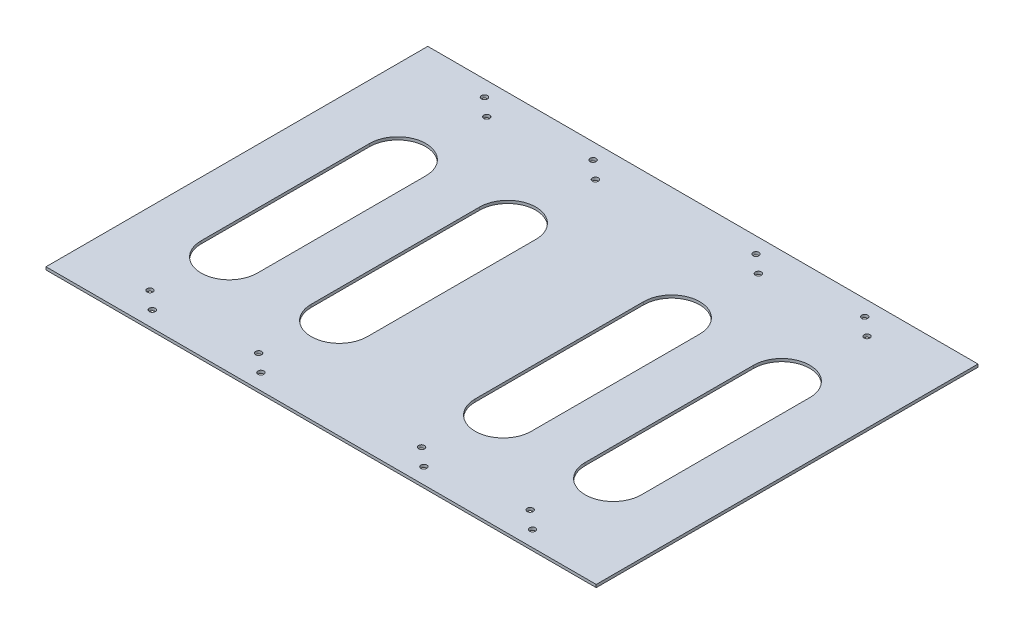
SolidWorks part; units mm, degrees
ref_plane "Front Plane" through (0, 0, 0) normal (0, 0, 1) x (1, 0, 0)
ref_plane "Top Plane" through (0, 0, 0) normal (0, 1, 0) x (1, 0, 0)
ref_plane "Right Plane" through (0, 0, 0) normal (1, 0, 0) x (0, 0, -1)
sketch "Sketch1" plane through (0, 0, 0) normal (0, 1, 0) x (1, 0, 0)
  line L1 (-196, 136) -> (196, 136)
  line L2 (-196, 136) -> (-196, -136)
  line L3 (-196, -136) -> (196, -136)
  line L4 (196, 136) -> (196, -136)
  line L5 (-196, 136) -> (196, -136) construction
  line L6 (-196, -136) -> (196, 136) construction
  point P0 (0, 0)
  dimension "D1" = 392
  dimension "D2" = 272
extrude "Boss-Extrude1" add sketch "Sketch1" along normal blind 2
sketch "Sketch2" plane through (0, 2, 0) normal (0, 1, 0) x (1, 0, 0)
  line L0 (-196, 0) -> (196, 0) construction
  line L1 (-196, 136) -> (-196, -136) construction
  line L2 (0, 136) -> (0, -139.5127) construction
  line L3 (196, 136) -> (-196, 136) construction
  line L6 (-196, -136) -> (196, -136) construction
  line L7 (196, -136) -> (196, 136) construction
  circle A2 centre (139.4, -124.77) radius 2.125
  circle A3 centre (126.5, -113.53) radius 2.125
  circle A9 centre (126.5, 124.77) radius 2.125
  circle A10 centre (139.4, 113.53) radius 2.125
  dimension "D1" = 12.9
  dimension "D2" = 4.25
  dimension "D3" = 4.25
  dimension "D10" = 12.9
  dimension "D11" = 11.23
  dimension "D14" = 56.6
  dimension "D8" = 4.25
  dimension "D9" = 4.25
  dimension "D4" = 56.6
  dimension "D5" = 11.24
  dimension "D6" = 11.23
  dimension "D12" = 11.24
extrude "Cut-Extrude1" cut sketch "Sketch2" against normal up to next
pattern_linear "LPattern1" count 2 spacing 77.4 along (-1, 0, 0) of "Cut-Extrude1"
pattern_linear "LPattern7" count 2 spacing 193.5 along (-1, 0, 0) of "Cut-Extrude1", "LPattern1"
sketch "Sketch3" plane through (0, 2, 0) normal (0, 1, 0) x (1, 0, 0)
  line L0 (-136.8, 55.3648) -> (-136.8, -64.6352) construction
  line L1 (-116.8, 55.3648) -> (-116.8, -64.6352)
  line L2 (-156.8, 55.3648) -> (-156.8, -64.6352)
  line L3 (-196, 136) -> (-196, -136) construction
  line L4 (-58.4, 55.3648) -> (-58.4, -64.6352) construction
  line L5 (-38.4, 55.3648) -> (-38.4, -64.6352)
  line L6 (-78.4, 55.3648) -> (-78.4, -64.6352)
  line L7 (0, 136) -> (0, -136) construction
  line L8 (196, 136) -> (-196, 136) construction
  line L9 (-196, -136) -> (196, -136) construction
  line L10 (58.4, 55.3648) -> (58.4, -64.6352) construction
  line L11 (38.4, 55.3648) -> (38.4, -64.6352)
  line L12 (78.4, 55.3648) -> (78.4, -64.6352)
  line L13 (136.8, 55.3648) -> (136.8, -64.6352) construction
  line L14 (116.8, 55.3648) -> (116.8, -64.6352)
  line L15 (156.8, 55.3648) -> (156.8, -64.6352)
  arc A0 (-116.8, 55.3648) -> (-156.8, 55.3648) centre (-136.8, 55.3648) ccw
  arc A1 (-156.8, -64.6352) -> (-116.8, -64.6352) centre (-136.8, -64.6352) ccw
  arc A2 (-38.4, 55.3648) -> (-78.4, 55.3648) centre (-58.4, 55.3648) ccw
  arc A3 (-78.4, -64.6352) -> (-38.4, -64.6352) centre (-58.4, -64.6352) ccw
  arc A4 (38.4, 55.3648) -> (78.4, 55.3648) centre (58.4, 55.3648) cw
  arc A5 (78.4, -64.6352) -> (38.4, -64.6352) centre (58.4, -64.6352) cw
  arc A6 (116.8, 55.3648) -> (156.8, 55.3648) centre (136.8, 55.3648) cw
  arc A7 (156.8, -64.6352) -> (116.8, -64.6352) centre (136.8, -64.6352) cw
  point P2 (-136.8, -4.6352)
  point P7 (-136.8, 75.3648)
  point P8 (-136.8, -84.6352)
  point P16 (-58.4, -4.6352)
  point P28 (58.4, -4.6352)
  point P35 (136.8, -4.6352)
  dimension "D4" = 55.3648
  dimension "D1" = 40
  dimension "D2" = 160
  dimension "D3" = 39.2
  dimension "D6" = 58.4
  dimension "D5" = 2
extrude "Cut-Extrude2" cut sketch "Sketch3" against normal through all
